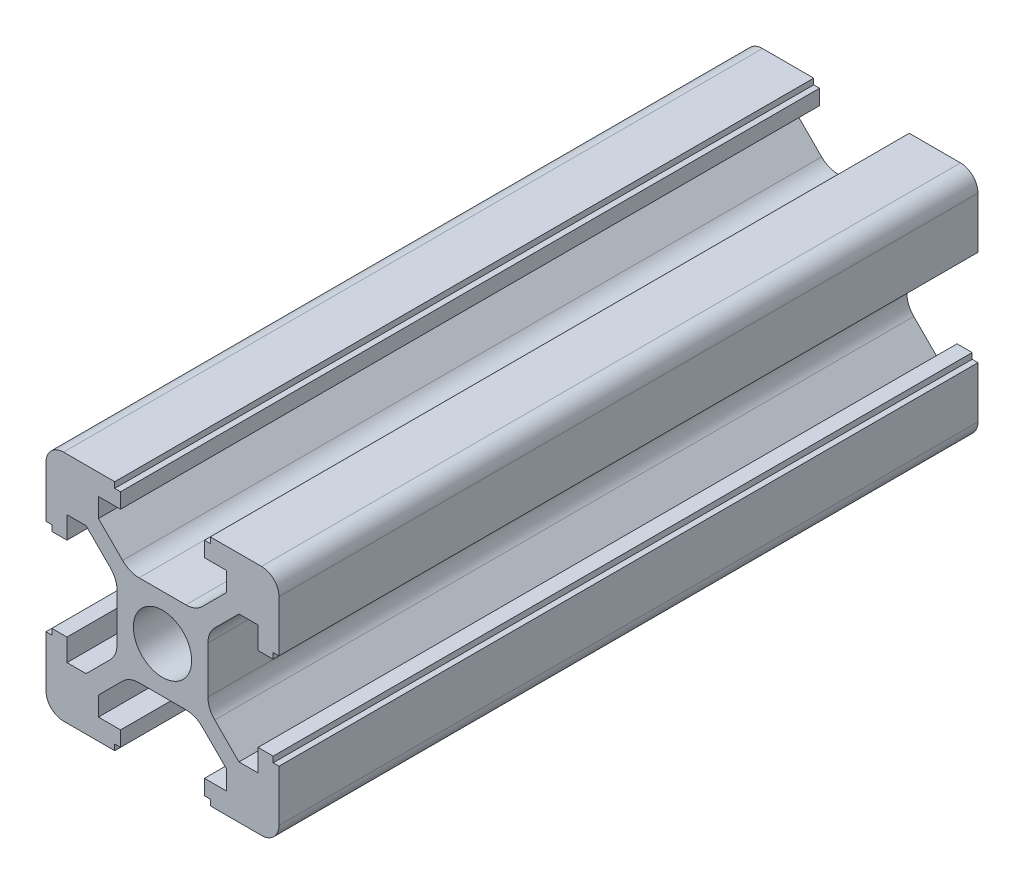
SolidWorks part; units mm, degrees
material "6063-O"
ref_plane "Front Plane" through (0, 0, 0) normal (0, 0, 1) x (1, 0, 0)
ref_plane "Top Plane" through (0, 0, 0) normal (0, 1, 0) x (1, 0, 0)
ref_plane "Right Plane" through (0, 0, 0) normal (1, 0, 0) x (0, 0, -1)
sketch "Sketch1" plane through (0, 0, 0) normal (0, 0, 1) x (1, 0, 0)
  line L0 (10, -4.1) -> (10, -8.5)
  line L1 (4.1, 10) -> (8.5, 10)
  line L2 (8.5, -10) -> (4.1, -10)
  line L3 (-8.5, -10) -> (-4.1, -10)
  line L4 (10, 8.5) -> (10, 4.1)
  line L7 (8.5, 10) -> (4.1, 10)
  line L8 (5.5, 6.5607) -> (3.4251, 4.4858)
  line L9 (8.5, 10) -> (4.1, 10)
  line L10 (3.9, 2.0109) -> (3.9, -2.0109)
  line L11 (2.0109, -3.9) -> (-2.0109, -3.9)
  line L12 (-3.9, -2.0109) -> (-3.9, 2.0109)
  line L13 (-2.0109, 3.9) -> (2.8393, 3.9)
  line L14 (2.5, 0) -> (22.2403, 0) construction
  line L15 (3.6, 9.5) -> (3.6, 8.2)
  line L16 (9.5, 3.6) -> (8.2, 3.6)
  line L17 (8.2, 3.6) -> (8.2, 5.5)
  line L18 (8.2, 5.5) -> (6.5607, 5.5)
  line L19 (10, -4.1) -> (10, -8.5)
  line L20 (4.1, 9.5) -> (3.6, 9.5)
  line L21 (4.1, 10) -> (4.1, 9.5)
  line L22 (8.5, 10) -> (4.1, 10)
  line L23 (10, 4.1) -> (9.5, 4.1)
  line L24 (9.5, 4.1) -> (9.5, 3.6)
  line L25 (5.5, 8.2) -> (5.5, 6.5607)
  line L26 (3.6, 8.2) -> (5.5, 8.2)
  line L27 (4.4858, 3.4251) -> (6.5607, 5.5)
  line L28 (10, -8.5) -> (10, -4.1)
  line L29 (6.5607, -5.5) -> (4.4858, -3.4251)
  line L30 (10, -8.5) -> (10, -4.1)
  line L31 (2.0109, -3.9) -> (-2.0109, -3.9)
  line L32 (3.9, 2.8393) -> (3.9, -2.0109)
  line L33 (9.5, -3.6) -> (8.2, -3.6)
  line L34 (3.6, -9.5) -> (3.6, -8.2)
  line L35 (3.6, -8.2) -> (5.5, -8.2)
  line L36 (5.5, -8.2) -> (5.5, -6.5607)
  line L37 (9.5, -4.1) -> (9.5, -3.6)
  line L38 (10, -4.1) -> (9.5, -4.1)
  line L39 (10, -8.5) -> (10, -4.1)
  line L40 (4.1, -10) -> (4.1, -9.5)
  line L41 (4.1, -9.5) -> (3.6, -9.5)
  line L42 (8.2, -5.5) -> (6.5607, -5.5)
  line L43 (8.2, -3.6) -> (8.2, -5.5)
  line L44 (3.4251, -4.4858) -> (5.5, -6.5607)
  line L45 (-4.1, -10) -> (-8.5, -10)
  line L46 (-10, -8.5) -> (-10, -4.1)
  line L47 (-8.5, -10) -> (-4.1, -10)
  line L48 (-5.5, -6.5607) -> (-3.4251, -4.4858)
  line L49 (-8.5, -10) -> (-4.1, -10)
  line L50 (-3.9, -2.0109) -> (-3.9, 2.0109)
  line L51 (2.0109, -3.9) -> (-2.0109, -3.9)
  line L52 (-3.6, -9.5) -> (-3.6, -8.2)
  line L53 (-9.5, -3.6) -> (-8.2, -3.6)
  line L54 (-8.2, -3.6) -> (-8.2, -5.5)
  line L55 (-8.2, -5.5) -> (-6.5607, -5.5)
  line L56 (-4.1, -9.5) -> (-3.6, -9.5)
  line L57 (-4.1, -10) -> (-4.1, -9.5)
  line L58 (-8.5, -10) -> (-4.1, -10)
  line L59 (-10, -4.1) -> (-9.5, -4.1)
  line L60 (-9.5, -4.1) -> (-9.5, -3.6)
  line L61 (-5.5, -8.2) -> (-5.5, -6.5607)
  line L62 (-3.6, -8.2) -> (-5.5, -8.2)
  line L63 (-4.4858, -3.4251) -> (-6.5607, -5.5)
  line L64 (-10, 4.1) -> (-10, 8.5)
  line L65 (-8.5, 10) -> (-4.1, 10)
  line L66 (-10, 8.5) -> (-10, 4.1)
  line L67 (-6.5607, 5.5) -> (-4.4858, 3.4251)
  line L68 (-10, 8.5) -> (-10, 4.1)
  line L69 (-2.0109, 3.9) -> (2.0109, 3.9)
  line L70 (-3.9, -2.0109) -> (-3.9, 2.0109)
  line L71 (-9.5, 3.6) -> (-8.2, 3.6)
  line L72 (-3.6, 9.5) -> (-3.6, 8.2)
  line L73 (-3.6, 8.2) -> (-5.5, 8.2)
  line L74 (-5.5, 8.2) -> (-5.5, 6.5607)
  line L75 (-9.5, 4.1) -> (-9.5, 3.6)
  line L76 (-10, 4.1) -> (-9.5, 4.1)
  line L77 (-10, 8.5) -> (-10, 4.1)
  line L78 (-4.1, 10) -> (-4.1, 9.5)
  line L79 (-4.1, 9.5) -> (-3.6, 9.5)
  line L80 (-8.2, 5.5) -> (-6.5607, 5.5)
  line L81 (-8.2, 3.6) -> (-8.2, 5.5)
  line L82 (-3.4251, 4.4858) -> (-5.5, 6.5607)
  line L83 (4.1, -10) -> (8.5, -10)
  arc A0 (2.0109, -3.9) -> (3.4251, -4.4858) centre (2.0109, -5.9) cw
  arc A1 (4.4858, -3.4251) -> (3.9, -2.0109) centre (5.9, -2.0109) cw
  arc A2 (3.9, 2.0109) -> (4.4858, 3.4251) centre (5.9, 2.0109) cw
  arc A3 (2.0109, 3.9) -> (3.4251, 4.4858) centre (2.0109, 5.9) ccw
  arc A4 (-2.0109, 3.9) -> (-3.4251, 4.4858) centre (-2.0109, 5.9) cw
  arc A5 (-4.4858, 3.4251) -> (-3.9, 2.0109) centre (-5.9, 2.0109) cw
  arc A6 (-3.4251, -4.4858) -> (-2.0109, -3.9) centre (-2.0109, -5.9) cw
  arc A7 (-3.9, -2.0109) -> (-4.4858, -3.4251) centre (-5.9, -2.0109) cw
  circle A8 centre (0, 0) radius 2.5
  arc A9 (-8.5, -10) -> (-10, -8.5) centre (-8.5, -8.5) cw
  arc A10 (-10, 8.5) -> (-8.5, 10) centre (-8.5, 8.5) cw
  arc A11 (8.5, 10) -> (10, 8.5) centre (8.5, 8.5) cw
  arc A12 (8.5, -10) -> (10, -8.5) centre (8.5, -8.5) ccw
  point P0 (0, 0)
  point P86 (0, 0)
  point P107 (10, -10)
  dimension "D3" = 2
  dimension "D5" = 5
  dimension "D2" = 1.5
  dimension "D8" = 1.5
  dimension "D6" = 4
  dimension "D7" = 6.1
  dimension "D11" = 0.5
  dimension "D12" = 0.5
extrude "Boss-Extrude2" add sketch "Sketch1" along normal blind 60
